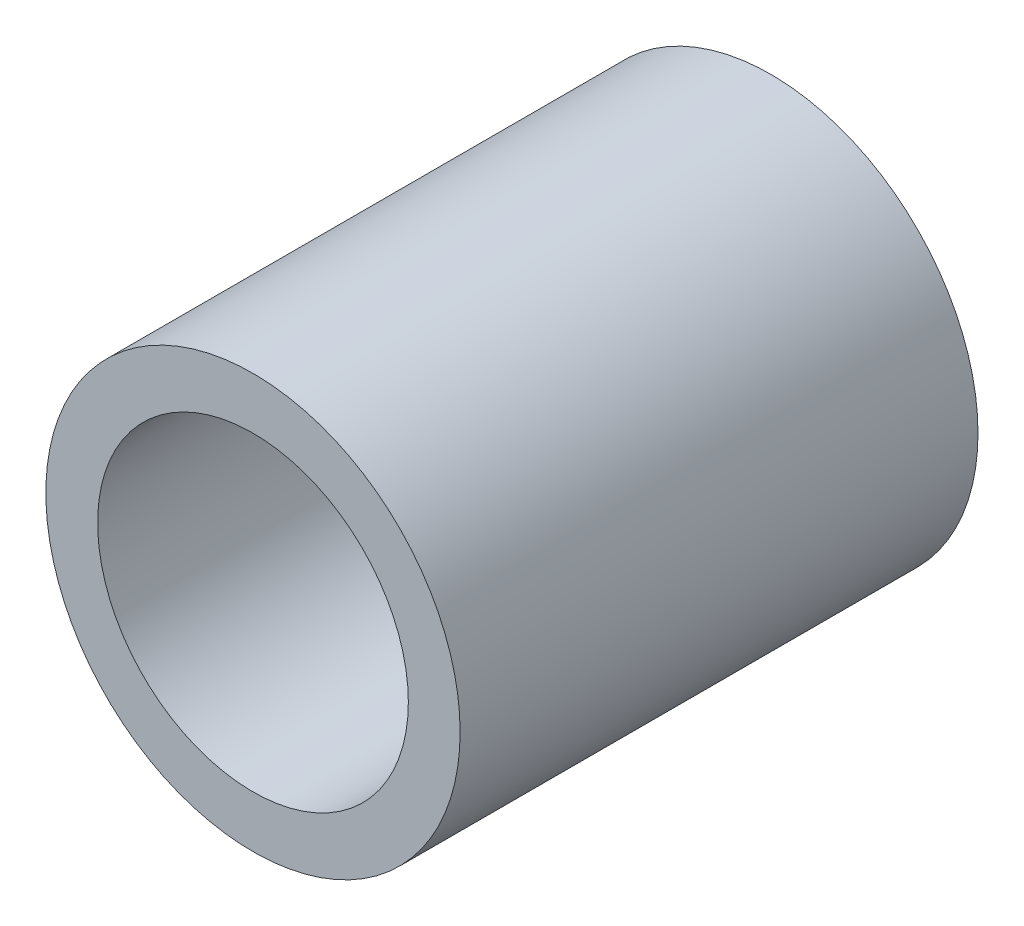
SolidWorks part; units mm, degrees
ref_plane "Plan de face" through (0, 0, 0) normal (0, 0, 1) x (1, 0, 0)
ref_plane "Plan de dessus" through (0, 0, 0) normal (0, 1, 0) x (1, 0, 0)
ref_plane "Plan de droite" through (0, 0, 0) normal (1, 0, 0) x (0, 0, -1)
sketch "Esquisse1" plane through (0, 0, 0) normal (0, 0, 1) x (1, 0, 0)
  circle A0 centre (-1.2603, 1.6851) radius 2.4
  dimension "D1" = 4.8
extrude "Boss.-Extru.1" add sketch "Esquisse1" along normal blind 6
sketch "Esquisse2" plane through (0, 0, 0) normal (0, 0, 1) x (1, 0, 0)
  circle A0 centre (-1.2603, 1.6851) radius 1.8
  dimension "D1" = 3.6
extrude "Enlèv. mat.-Extru.1" cut sketch "Esquisse2" along normal blind 6
